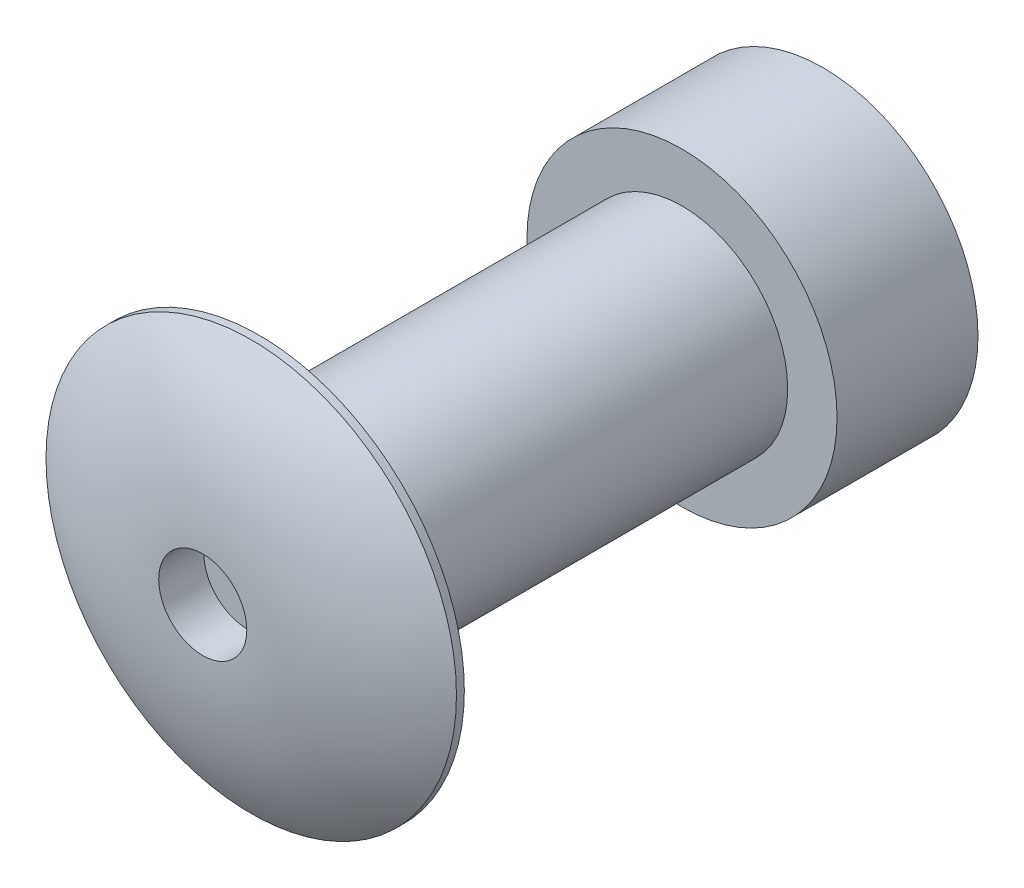
SolidWorks part; units mm, degrees
material "6061-T6 (SS)"
ref_plane "Front" through (0, 0, 0) normal (0, 0, 1) x (1, 0, 0)
ref_plane "Top" through (0, 0, 0) normal (0, 1, 0) x (1, 0, 0)
ref_plane "Right" through (0, 0, 0) normal (1, 0, 0) x (0, 0, -1)
sketch "layout" plane through (0, 0, 0) normal (1, 0, 0) x (0, 0, -1)
  line L0 (-15.5575, 0) -> (-1.27, 0) construction
  line L1 (-1.27, 0) -> (0, 0) construction
  line L2 (0, 0) -> (9.525, 0) construction
  line L3 (9.525, 0) -> (11.43, 0) construction
  line L8 (0, 4.6228) -> (0, -4.6228) construction
  line L9 (9.525, 2.3813) -> (9.525, -2.3813) construction
  dimension "D5" = 1.905
sketch "Sketch2" plane through (0, 0, 0) normal (1, 0, 0) x (0, 0, -1)
  line L0 (-15.5575, 0) -> (-15.5575, 0.9922) construction
  line L1 (-1.27, 0.9922) -> (-1.27, 0)
  line L2 (9.525, 0) -> (-1.27, 0)
  line L3 (0, 0) -> (0, 4.6228) construction
  line L4 (-1.27, 0) -> (-1.27, -1.8472) construction
  line L5 (9.525, 2.3813) -> (0, 2.3812)
  line L7 (10.0012, 2.3813) -> (10.0012, -1.9844) construction
  line L8 (-1.27, 0) -> (9.525, 0) construction
  line L9 (11.43, 0) -> (11.43, 2.3813) construction
  line L10 (9.525, 2.3813) -> (10.0012, 2.3813) construction
  line L11 (10.0012, 2.3813) -> (10.4775, 2.3813) construction
  line L12 (-7.6006, 0) -> (-15.5575, 0) construction
  line L13 (-1.27, 0.9922) -> (-1.27, 0) construction
  line L14 (10.4775, 2.3813) -> (10.9538, 2.3813) construction
  line L15 (10.9538, 2.3813) -> (11.43, 2.3813) construction
  line L16 (-1.27, 0) -> (9.525, 0) construction
  line L17 (9.525, 2.3813) -> (9.525, 3.4925)
  line L18 (10.0012, 0) -> (11.43, 0) construction
  line L19 (0, 2.3812) -> (0, 4.6228)
  line L20 (-1.27, 0.9922) -> (-15.5575, 0.9922) construction
  line L21 (-15.5575, 0) -> (-1.27, 0) construction
  line L22 (0, 4.6228) -> (-0.1778, 4.6228)
  line L23 (9.525, 0) -> (10.0012, 0) construction
  line L24 (9.525, 3.4925) -> (12.7, 3.4925)
  line L25 (12.7, 3.4925) -> (12.7, 0)
  line L26 (9.525, 0) -> (12.7, 0)
  arc A2 (-0.1778, 4.6228) -> (-1.27, 0.9922) centre (5.3104, 0.9922) ccw
  dimension "D1" = 0.1778
  dimension "D2" = 2.3813
  dimension "D3" = 0.9922
  dimension "D4" = 3.175
  dimension "D5" = 6.985
revolve "Revolve1" add sketch "Sketch2" angle 360 about L12
sketch "Sketch4" plane through (0, 0, 1.27) normal (0, 0, 1) x (1, 0, 0)
  circle A1 centre (0, 0) radius 0.9922 construction
  circle A2 centre (0, 0) radius 0.9922
extrude "Cut-Extrude1" cut sketch "Sketch4" against normal blind 1.016
sketch "Sketch3" plane through (0, 0, -12.7) normal (0, 0, -1) x (-1, 0, 0)
  circle A1 centre (0, 0) radius 0.9922 construction
  circle A2 centre (0, 0) radius 0.9922
extrude "Cut-Extrude2" cut sketch "Sketch3" against normal blind 2.54
other "Freeze***"
equation "\"D5@layout\"=\"Head Height@layout\"*1.5"
equation "\"D9@layout\"=\"length@layout\"*1.5"
